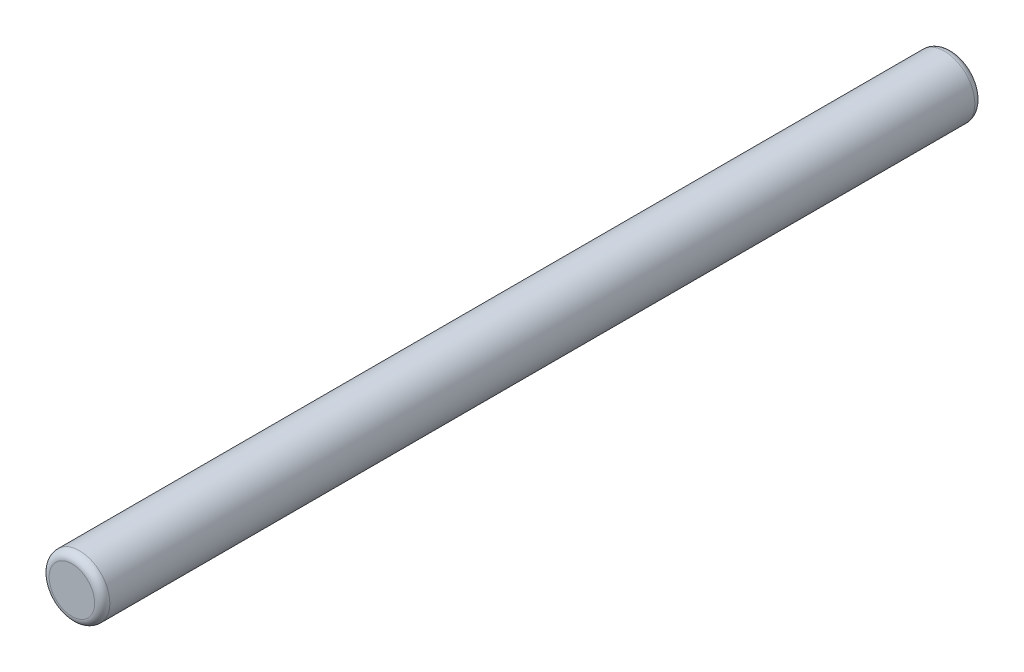
SolidWorks part; units mm, degrees
material "Alloy Steel"
ref_plane "Front Plane" through (0, 0, 0) normal (0, 0, 1) x (1, 0, 0)
ref_plane "Top Plane" through (0, 0, 0) normal (0, 1, 0) x (1, 0, 0)
ref_plane "Right Plane" through (0, 0, 0) normal (1, 0, 0) x (0, 0, -1)
sketch "Sketch1" plane through (0, 0, 0) normal (0, 0, 1) x (1, 0, 0)
  circle A0 centre (0, 0) radius 6.35
  dimension "D1" = 12.7
extrude "Boss-Extrude1" add sketch "Sketch1" along normal blind 184.15
fillet "Fillet1" radius 1.5875 2 edges at (6.35, 0, 0) (6.35, 0, 184.15)
